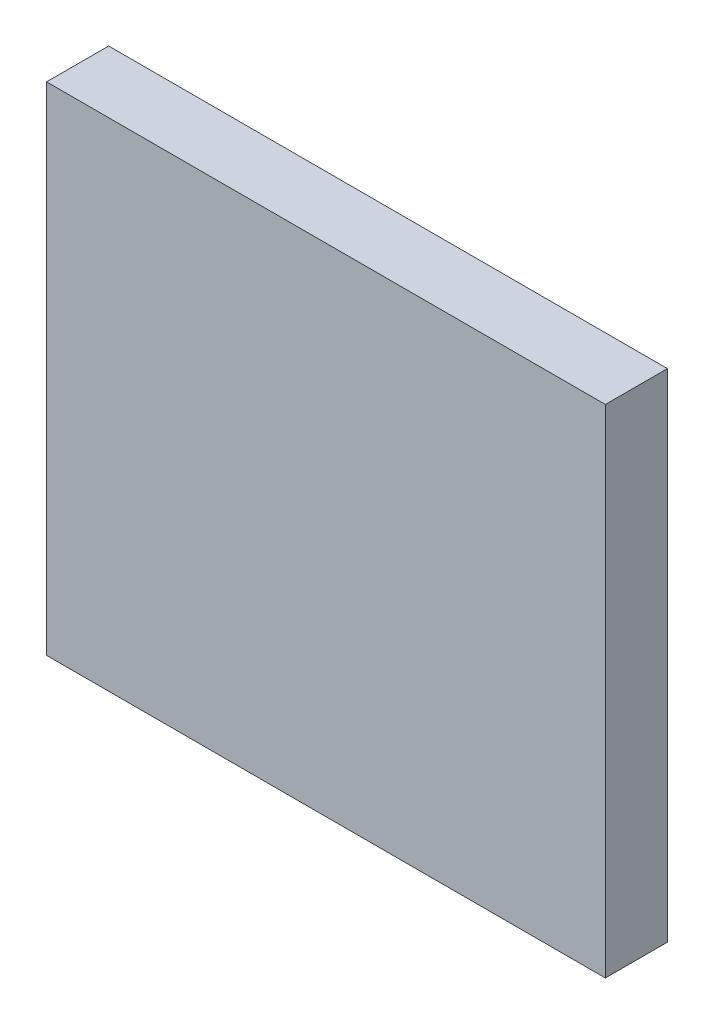
SolidWorks part; units mm, degrees
ref_plane "Plan de face" through (0, 0, 0) normal (0, 0, 1) x (1, 0, 0)
ref_plane "Plan de dessus" through (0, 0, 0) normal (0, 1, 0) x (1, 0, 0)
ref_plane "Plan de droite" through (0, 0, 0) normal (1, 0, 0) x (0, 0, -1)
sketch "Esquisse1" plane through (0, 0, 0) normal (0, 0, 1) x (1, 0, 0)
  line L1 (0, 0) -> (90, 0)
  line L2 (0, 0) -> (0, 80)
  line L3 (0, 80) -> (90, 80)
  line L4 (90, 0) -> (90, 80)
  dimension "D1" = 90
  dimension "D2" = 80
extrude "Boss.-Extru.1" add sketch "Esquisse1" along normal blind 10
sketch "Esquisse2" [suppressed] plane through (0, 0, 10) normal (0, 0, 1) x (1, 0, 0)
  line L0 (45, 0) -> (45, 80) construction
  line L1 (0, 0) -> (90, 0) construction
  line L2 (90, 80) -> (0, 80) construction
  circle A0 centre (45, 40) radius 19
  dimension "D1" = 70
extrude "Enlèv. mat.-Extru.1" [suppressed] cut sketch "Esquisse2" against normal through all both and the other way through all
